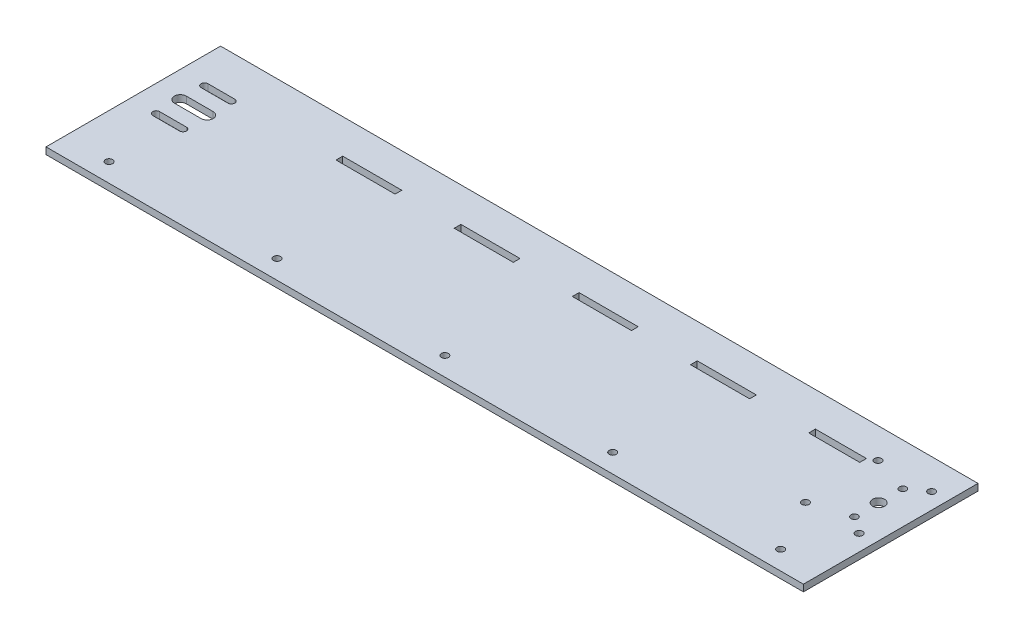
SolidWorks part; units mm, degrees
ref_plane "Front Plane" through (0, 0, 0) normal (0, 0, 1) x (1, 0, 0)
ref_plane "Top Plane" through (0, 0, 0) normal (0, 1, 0) x (1, 0, 0)
ref_plane "Right Plane" through (0, 0, 0) normal (1, 0, 0) x (0, 0, -1)
sketch "Sketch1" plane through (0, 0, 0) normal (0, 1, 0) x (1, 0, 0)
  line L0 (0, 0) -> (0, 40)
  line L3 (0, 40) -> (0, 65)
  line L5 (0, 0) -> (0, -65)
  line L6 (0, -65) -> (-524.5, -65)
  line L7 (-524.5, -65) -> (-564, -65)
  line L9 (-57.5595, 39.5) -> (-57.5595, 34.5)
  line L13 (-544.5, 36.05) -> (-524.5, 36.05)
  line L14 (-544.5, 30.95) -> (-524.5, 30.95)
  line L15 (-524.5, 0.05) -> (-544.5, 0.05)
  line L16 (-524.5, -5.05) -> (-544.5, -5.05)
  line L18 (-544.5, 20) -> (-524.5, 20)
  line L19 (-544.5, 11) -> (-524.5, 11)
  line L20 (-564, -65) -> (-564, 65)
  line L22 (0, 65) -> (-564, 65)
  line L24 (-564, -65) -> (-531, -65)
  line L28 (-57.5595, 34.5) -> (-95.5595, 34.5)
  line L29 (-95.5595, 34.5) -> (-95.5595, 39.5)
  line L30 (-95.5595, 39.5) -> (-57.5595, 39.5)
  line L31 (-139.5595, 39.5) -> (-139.5595, 34.5)
  line L32 (-139.5595, 34.5) -> (-183.5595, 34.5)
  line L33 (-183.5595, 34.5) -> (-183.5595, 39.5)
  line L34 (-183.5595, 39.5) -> (-139.5595, 39.5)
  line L35 (-227.5595, 39.5) -> (-227.5595, 34.5)
  line L36 (-227.5595, 34.5) -> (-271.5595, 34.5)
  line L37 (-271.5595, 34.5) -> (-271.5595, 39.5)
  line L38 (-271.5595, 39.5) -> (-227.5595, 39.5)
  line L39 (-315.5595, 39.5) -> (-315.5595, 34.5)
  line L40 (-315.5595, 34.5) -> (-359.5595, 34.5)
  line L41 (-359.5595, 34.5) -> (-359.5595, 39.5)
  line L42 (-359.5595, 39.5) -> (-315.5595, 39.5)
  line L43 (-403.5595, 39.5) -> (-403.5595, 34.5)
  line L44 (-403.5595, 34.5) -> (-447.5595, 34.5)
  line L45 (-447.5595, 34.5) -> (-447.5595, 39.5)
  line L48 (-447.5595, 39.5) -> (-403.5595, 39.5)
  circle A0 centre (-12, 42.5) radius 2.65
  circle A1 centre (-24.5, 33.5) radius 2.55
  circle A2 centre (-24.5, -2.5) radius 2.55
  circle A3 centre (-24.5, 15.5) radius 4.5
  arc A4 (-524.5, 30.95) -> (-524.5, 36.05) centre (-524.5, 33.5) ccw
  circle A5 centre (-12, -11.5) radius 2.65
  arc A6 (-524.5, -5.05) -> (-524.5, 0.05) centre (-524.5, -2.5) ccw
  arc A7 (-524.5, 11) -> (-524.5, 20) centre (-524.5, 15.5) ccw
  arc A8 (-544.5, 36.05) -> (-544.5, 30.95) centre (-544.5, 33.5) ccw
  arc A9 (-544.5, 20) -> (-544.5, 11) centre (-544.5, 15.5) ccw
  arc A10 (-544.5, 0.05) -> (-544.5, -5.05) centre (-544.5, -2.5) ccw
  circle A11 centre (-531, -51) radius 2.65
  circle A12 centre (-406, -51) radius 2.65
  circle A13 centre (-281, -51) radius 2.65
  circle A14 centre (-156, -51) radius 2.65
  circle A15 centre (-52, -11.5) radius 2.65
  circle A16 centre (-52, 42.5) radius 2.65
  circle A19 centre (-31, -51) radius 2.65
  dimension "D4" = 18
  dimension "D6" = 9
  dimension "D8" = 5.1
  dimension "D9" = 5.1
  dimension "D13" = 65
  dimension "D19" = 5.1
  dimension "D20" = 5.1
  dimension "D21" = 9
  dimension "D24" = 5.1
  dimension "D25" = 20
  dimension "D26" = 9
  dimension "D30" = 40
  dimension "D14" = 5.3
  dimension "D28" = 5.3
  dimension "D5" = 18
  dimension "D10" = 25
  dimension "D11" = 40
  dimension "D15" = 524.5
  dimension "D16" = 39.5
  dimension "D17" = 18
  dimension "D18" = 18
  dimension "D22" = 20
  dimension "D23" = 20
  dimension "D27" = 33
  dimension "D29" = 14
  dimension "D32" = 38
  dimension "D34" = 44
  dimension "D35" = 44
  dimension "D36" = 44
  dimension "D37" = 44
  dimension "D39" = 44
  dimension "D40" = 44
  dimension "D41" = 44
  dimension "D42" = 44
  dimension "D45" = 125
  dimension "D46" = 125
  dimension "D47" = 125
  dimension "D48" = 125
extrude "Boss-Extrude1" add sketch "Sketch1" along normal blind 5 contours L3 L22 L20 L7 L6 L5 L0 A19 A5 A3 A2 A1 A0 L29 L30 L9 L28 L33 L34 L31 L32 L37 L38 L35 L36 L41 L42 L39 L40 L45 L48 L43 L44 A8 L13 A4 L14
